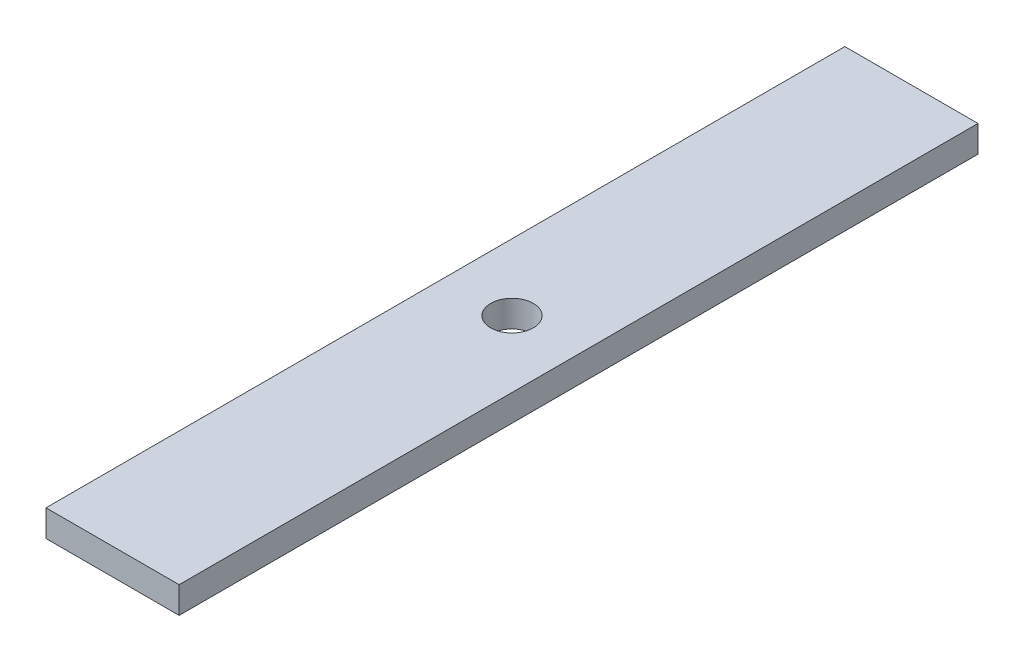
SolidWorks part; units mm, degrees
material "AISI 1045 Steel, cold drawn"
ref_plane "Front Plane" through (0, 0, 0) normal (0, 0, 1) x (1, 0, 0)
ref_plane "Top Plane" through (0, 0, 0) normal (0, 1, 0) x (1, 0, 0)
ref_plane "Right Plane" through (0, 0, 0) normal (1, 0, 0) x (0, 0, -1)
sketch "Sketch1" plane through (0, 0, 0) normal (0, 0, 1) x (1, 0, 0)
  line L1 (-12.5, 2.5) -> (12.5, 2.5)
  line L2 (-12.5, 2.5) -> (-12.5, -2.5)
  line L3 (-12.5, -2.5) -> (12.5, -2.5)
  line L4 (12.5, 2.5) -> (12.5, -2.5)
  point P4 (12.5, 0)
  point P6 (0, 2.5)
  dimension "D1" = 25
  dimension "D2" = 5
extrude "Boss-Extrude1" add sketch "Sketch1" along normal mid plane 212
sketch "Sketch2" plane through (0, 2.5, 0) normal (0, 1, 0) x (1, 0, 0)
  line L0 (0, 0) -> (35.2363, 0) construction
  circle A0 centre (0, 87.5) radius 4
  circle A1 centre (0, 0) radius 4
  circle A2 centre (0, -87.5) radius 4
  dimension "D1" = 8
  dimension "D2" = 175
extrude "Holes for 20mm strip ONLY" cut sketch "Sketch2" against normal through all
sketch "Sketch3" [suppressed] plane through (0, 2.5, 0) normal (0, 1, 0) x (1, 0, 0)
  line L0 (0, 0) -> (65.8821, 0) construction
  line L1 (15, -175) -> (-15, -175) construction
  circle A0 centre (0, -50) radius 2.5
  circle A1 centre (0, -150) radius 2.5
  circle A2 centre (0, 150) radius 2.5
  circle A3 centre (0, 50) radius 2.5
  point P7 (0, -175)
  dimension "D2" = 5
  dimension "D1" = 100
  dimension "D3" = 300
extrude "Cut-Extrude1" [suppressed] cut sketch "Sketch3" against normal through all
sketch "Sketch4" [suppressed] plane through (0, 2.5, 0) normal (0, 1, 0) x (1, 0, 0)
  line L0 (-10, -106) -> (-10, 106) construction
  line L1 (10, -26) -> (-10, -26)
  line L2 (10, -26) -> (10, 26)
  line L3 (10, 26) -> (-10, 26)
  line L4 (-10, -26) -> (-10, 26)
  line L5 (10, -26) -> (-10, 26) construction
  line L6 (10, 26) -> (-10, -26) construction
  point P0 (0, 0)
  dimension "D1" = 52
extrude "Cut-Extrude2" [suppressed] cut sketch "Sketch4" against normal through all flip side to cut
sketch "Sketch5" plane through (0, 2.5, 0) normal (0, 1, 0) x (1, 0, 0)
  line L1 (-25.7525, -75) -> (25.7525, -75)
  line L2 (-25.7525, -75) -> (-25.7525, 75)
  line L3 (-25.7525, 75) -> (25.7525, 75)
  line L4 (25.7525, -75) -> (25.7525, 75)
  line L5 (-25.7525, -75) -> (25.7525, 75) construction
  line L6 (-25.7525, 75) -> (25.7525, -75) construction
  point P0 (0, 0)
  dimension "D1" = 150
extrude "Cut-Extrude3" cut sketch "Sketch5" against normal through all flip side to cut
